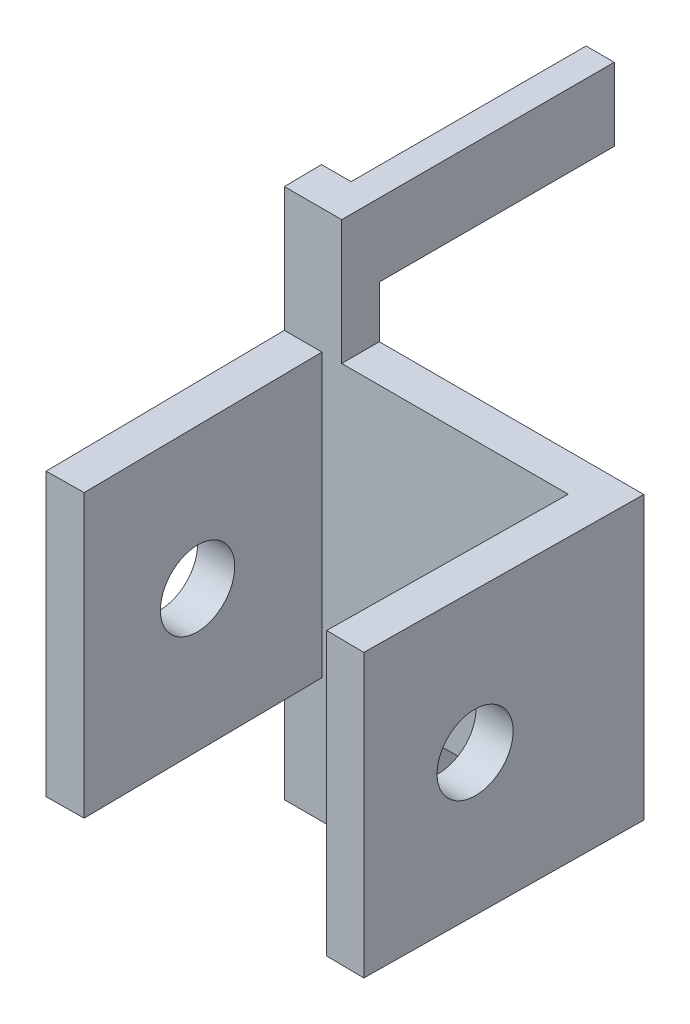
SolidWorks part; units mm, degrees
ref_plane "Front Plane" through (0, 0, 0) normal (0, 0, 1) x (1, 0, 0)
ref_plane "Top Plane" through (0, 0, 0) normal (0, 1, 0) x (1, 0, 0)
ref_plane "Right Plane" through (0, 0, 0) normal (1, 0, 0) x (0, 0, -1)
sketch "Sketch1" plane through (0, 0, 0) normal (0, 1, 0) x (1, 0, 0)
  line L0 (-12.8, -12.8) -> (-13.1, 12.8)
  line L1 (-12.8, 12.8) -> (12.8, 12.8) construction
  line L2 (-12.8, 12.8) -> (-12.8, -12.8) construction
  line L4 (12.8, 12.8) -> (12.8, -12.6) construction
  line L5 (-13.1, 12.8) -> (13.1, 12.8)
  line L6 (13.1, 12.8) -> (12.8, -12.6)
  line L7 (-16.7997, -12.8469) -> (-17.1471, 16.8)
  line L8 (-17.1471, 16.8) -> (17.1475, 16.8)
  line L9 (17.1475, 16.8) -> (16.7997, -12.6472)
  line L11 (-16.7997, -12.8469) -> (-12.8, -12.8)
  line L12 (12.8, -12.6) -> (16.7997, -12.6472)
  dimension "D1" = 25.6
  dimension "D2" = 25.4
  dimension "D3" = 0.3
  dimension "D4" = 0.3
  dimension "D5" = 4
extrude "Boss-Extrude1" add sketch "Sketch1" along normal blind 30
sketch "Sketch2" plane through (0, 30, 0) normal (0, 1, 0) x (1, 0, 0)
  line L0 (0.0002, 16.8) -> (0.0002, 30.8112) construction
  line L1 (17.1475, 16.8) -> (-17.1471, 16.8) construction
  line L2 (0.0002, 36.8) -> (-4.0998, 36.8) construction
  line L3 (0.0002, 36.8) -> (2.1002, 36.8) construction
  line L4 (-4.0998, 36.8) -> (-4.0998, 23.7851)
  line L5 (-2.0998, 36.8) -> (-2.0998, 23.7851)
  line L6 (-11.0849, 16.8) -> (-5.4334, 16.8)
  line L7 (-4.0998, 36.8) -> (-2.0998, 36.8)
  line L8 (4.1002, 36.8) -> (2.1002, 36.8)
  line L9 (11.0853, 16.8) -> (5.4337, 16.8)
  line L10 (2.1002, 36.8) -> (2.1002, 23.7851)
  line L11 (4.1002, 36.8) -> (4.1002, 23.7851)
  arc A0 (-4.0998, 23.7851) -> (-11.0849, 16.8) centre (-11.0849, 23.7851) cw
  arc A1 (-2.0998, 23.7851) -> (-5.4334, 16.8) centre (-11.0849, 23.7851) cw
  arc A2 (-2.0998, 23.7851) -> (-11.0849, 14.8) centre (-11.0849, 23.7851) cw construction
  arc A3 (4.1002, 23.7851) -> (11.0853, 16.8) centre (11.0853, 23.7851) ccw
  arc A4 (2.1002, 23.7851) -> (5.4337, 16.8) centre (11.0853, 23.7851) ccw
  dimension "D1" = 20
  dimension "D2" = 4.1
  dimension "D3" = 2
sketch "Sketch3" plane through (16.9467, 0, 0.2002) normal (0.9999, 0, 0.0118) x (0.0118, 0, -0.9999)
  line L0 (-12.448, 0) -> (10.952, 0) construction
  line L1 (-0.748, 0) -> (-0.748, 30) construction
  line L5 (-12.448, 30) -> (17.0013, 30) construction
  circle A0 centre (-0.748, 15) radius 4
  dimension "D1" = 11.7
extrude "Cut-Extrude1" cut sketch "Sketch3" against normal blind 40
sketch "Sketch4" plane through (0, 0, -16.8) normal (0, 0, -1) x (-1, 0, 0)
  line L0 (17.1471, 0) -> (-17.1475, 30) construction
  line L1 (-0.0002, 15) -> (10.9998, 15) construction
  line L2 (10.9998, -5.5) -> (10.9998, 35.5)
  line L3 (10.9998, 35.5) -> (13.9998, 35.5)
  line L4 (10.9998, -5.5) -> (13.9998, -5.5)
  line L6 (13.9998, 35.5) -> (13.9998, -5.5)
  point P8 (10.9998, 15)
  point P9 (0, 0)
  dimension "D1" = 3
extrude "Boss-Extrude2" add sketch "Sketch4" against normal blind 4
sketch "Sketch5" plane through (0, 0, -16.8) normal (0, 0, -1) x (-1, 0, 0)
  line L1 (13.9998, 35.5) -> (13.9998, 43.25)
  line L11 (10.9998, 35.5) -> (10.9998, 43.25)
  line L17 (10.9998, 35.5) -> (13.9998, 35.5)
  line L18 (10.9998, 43.25) -> (13.9998, 43.25)
  line L21 (17.1471, 15) -> (-23.8791, 15) construction
  line L22 (17.1471, 30) -> (17.1471, 0) construction
  line L23 (10.9998, -13.25) -> (13.9998, -13.25)
  line L24 (10.9998, -5.5) -> (13.9998, -5.5)
  line L25 (10.9998, -5.5) -> (10.9998, -13.25)
  line L26 (13.9998, -5.5) -> (13.9998, -13.25)
extrude "Boss-Extrude3" add sketch "Sketch5" against normal blind 4 and the other way blind 25
sketch "Sketch6" plane through (-13.9998, 0, 0) normal (-1, 0, 0) x (0, 0, 1)
  line L0 (-16.8, 43.25) -> (-16.8, -13.25)
  line L1 (-41.8, 43.25) -> (-12.8, 43.25) construction
  line L2 (-12.8, -13.25) -> (-12.8, 43.25)
  line L3 (-12.8, -13.25) -> (-16.8, -13.25)
  line L4 (-12.8, 43.25) -> (-16.8, 43.25)
extrude "Boss-Extrude4" add sketch "Sketch6" along normal up to surface (3.1005 mm away)
